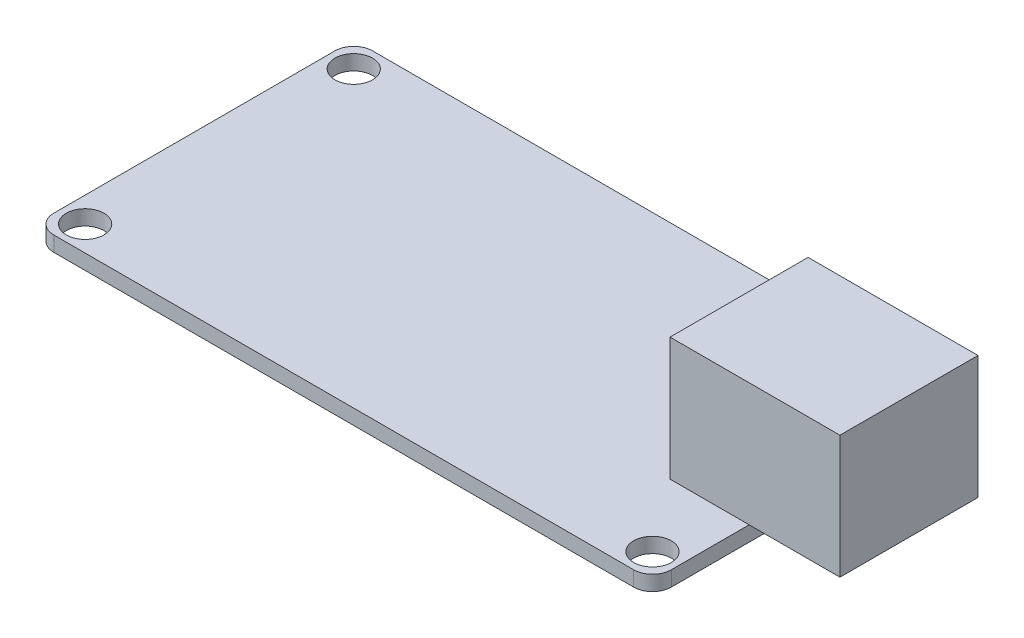
SolidWorks part; units mm, degrees
ref_plane "Plan de face" through (0, 0, 0) normal (0, 0, 1) x (1, 0, 0)
ref_plane "Plan de dessus" through (0, 0, 0) normal (0, 1, 0) x (1, 0, 0)
ref_plane "Plan de droite" through (0, 0, 0) normal (1, 0, 0) x (0, 0, -1)
sketch "Esquisse1" plane through (0, 0, 0) normal (0, 1, 0) x (1, 0, 0)
  line L0 (-24.6, 12.7) -> (-22.6, 12.7) construction
  line L1 (-24.6, -12.7) -> (24.6, -12.7)
  line L2 (-24.6, -12.7) -> (-24.6, 12.7)
  line L3 (-24.6, 12.7) -> (24.6, 12.7)
  line L4 (24.6, -12.7) -> (24.6, 12.7)
  line L5 (-24.6, -12.7) -> (24.6, 12.7) construction
  line L6 (-24.6, 12.7) -> (24.6, -12.7) construction
  line L7 (-22.6, 12.7) -> (-22.6, -12.7) construction
  line L8 (-24.6, 12.7) -> (-24.6, 10.7) construction
  line L9 (-24.6, 10.7) -> (24.6, 10.7) construction
  line L10 (24.6, 12.7) -> (22.6, 12.7) construction
  line L11 (22.6, 12.7) -> (22.6, -12.7) construction
  line L12 (24.6, -12.7) -> (24.6, -10.7) construction
  line L13 (24.6, -10.7) -> (-24.6, -10.7) construction
  circle A0 centre (22.6, 10.7) radius 1.5
  circle A1 centre (22.6, -10.7) radius 1.5
  circle A2 centre (-22.6, -10.7) radius 1.5
  circle A3 centre (-22.6, 10.7) radius 1.5
  point P0 (0, 0)
  dimension "D1" = 25.4
  dimension "D2" = 49.2
extrude "Boss.-Extru.1" add sketch "Esquisse1" along normal blind 1.2
fillet "Congé1" radius 1.5 1 edges at (24.6, 0.6, 12.7)
fillet "Congé2" radius 1.5 1 edges at (-24.6, 0.6, 12.7)
fillet "Congé3" radius 1.5 1 edges at (24.6, 0.6, -12.7)
fillet "Congé4" radius 1.5 1 edges at (-24.6, 0.6, -12.7)
sketch "Esquisse3" plane through (1.4308, 1.2, 0.9356) normal (0, 1, 0) x (1, 0, 0)
  line L0 (-26.0308, 0.9356) -> (23.6336, 0.9356) construction
  line L1 (30.4008, 6.9364) -> (16.8664, 6.9364)
  line L2 (30.4008, 6.9364) -> (30.4008, -4.0636)
  line L3 (30.4008, -4.0636) -> (16.8664, -4.0636)
  line L4 (16.8664, 6.9364) -> (16.8664, -4.0636)
  line L5 (-26.0308, 12.1356) -> (-26.0308, -10.2644) construction
  line L6 (30.4008, 1.4364) -> (16.8664, 1.4364) construction
  dimension "D1" = 11
extrude "Boss.-Extru.2" add sketch "Esquisse3" along normal blind 9.8
